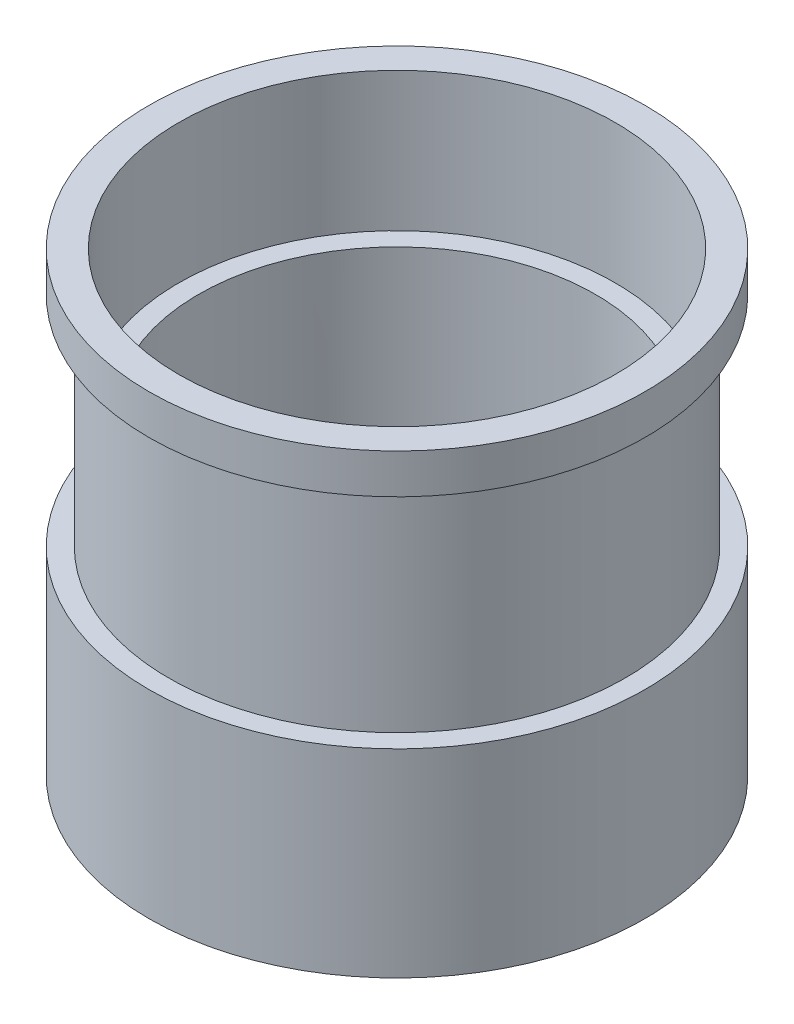
SolidWorks part; units mm, degrees
ref_plane "Alzado" through (0, 0, 0) normal (0, 0, 1) x (1, 0, 0)
ref_plane "Planta" through (0, 0, 0) normal (0, 1, 0) x (1, 0, 0)
ref_plane "Vista lateral" through (0, 0, 0) normal (1, 0, 0) x (0, 0, -1)
sketch "Croquis1" plane through (0, 0, 0) normal (0, 1, 0) x (1, 0, 0)
  circle A0 centre (0, 0) radius 12.5
  dimension "D1" = 25
extrude "Saliente-Extruir1" add sketch "Croquis1" along normal mid plane 23
sketch "Croquis2" plane through (0, 11.5, 0) normal (0, 1, 0) x (1, 0, 0)
  circle A0 centre (0, 0) radius 11
  dimension "D1" = 22
extrude "Cortar-Extruir1" cut sketch "Croquis2" against normal blind 7
sketch "Croquis3" plane through (0, 0, 0) normal (0, 1, 0) x (1, 0, 0)
  circle A0 centre (0, 0) radius 10
  dimension "D1" = 20
extrude "Cortar-Extruir2" cut sketch "Croquis3" against normal through all both and the other way through all
mirror "Simetría1" about plane through (0, 0, 0) normal (0, 1, 0) of "Cortar-Extruir1"
ref_axis "Eje1" through (0, -12.65, 0) along (0, 1, 0)
sketch "Croquis4" plane through (0, 0, 0) normal (0, 0, 1) x (1, 0, 0)
  line L0 (12.5, -11.5) -> (12.5, 11.5) construction
  line L1 (12.5, 9.5) -> (11.5, 9.5)
  line L2 (12.5, 9.5) -> (12.5, -1.5)
  line L3 (12.5, -1.5) -> (11.5, -1.5)
  line L4 (11.5, 9.5) -> (11.5, -1.5)
  line L5 (12.5, 11.5) -> (-12.5, 11.5) construction
  dimension "D1" = 2
  dimension "D2" = 1
  dimension "D3" = 11
revolve "Cortar-Revolución1" cut sketch "Croquis4" angle 360 about axis through (0, -12.65, 0) along (0, 1, 0)
